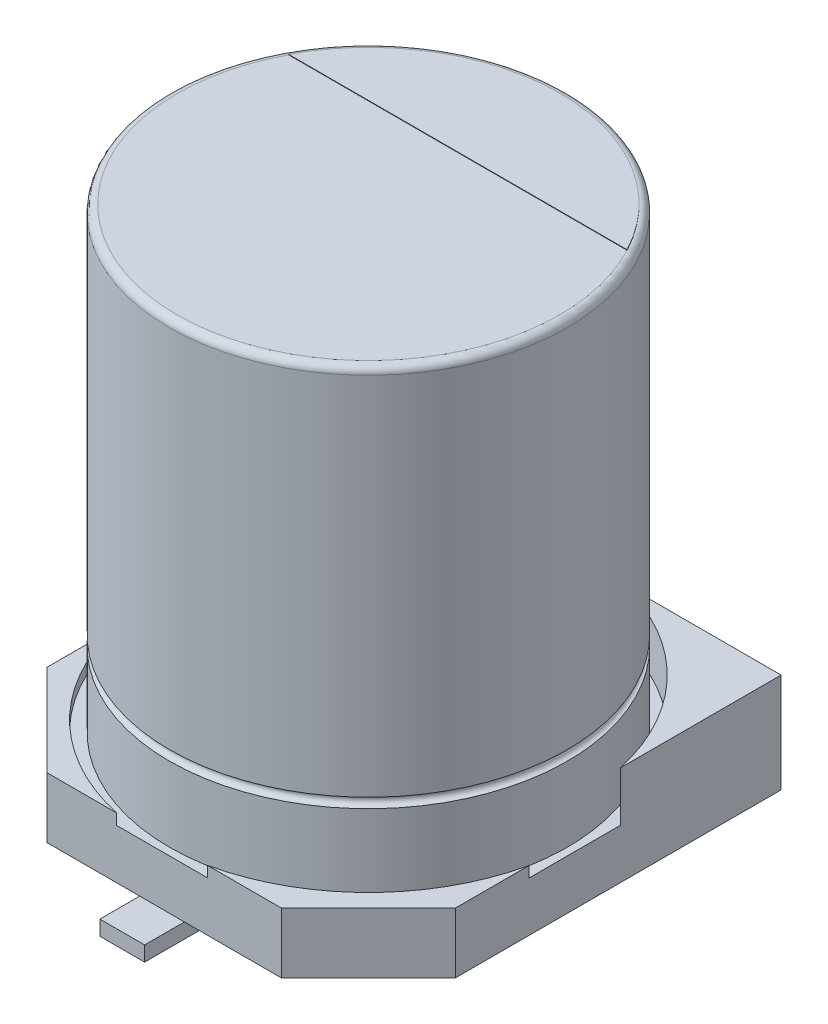
SolidWorks part; units mm, degrees
ref_plane "Front Plane" through (0, 0, 0) normal (0, 0, 1) x (1, 0, 0)
ref_plane "Top Plane" through (0, 0, 0) normal (0, 1, 0) x (1, 0, 0)
ref_plane "Right Plane" through (0, 0, 0) normal (1, 0, 0) x (0, 0, -1)
sketch "Sketch1" plane through (0, 0, 0) normal (0, 1, 0) x (1, 0, 0)
  line L0 (-4.15, 4.15) -> (4.15, 4.15)
  line L1 (4.15, 4.15) -> (4.15, -2.4026)
  line L2 (4.15, -2.4026) -> (2.4026, -4.15)
  line L3 (2.4026, -4.15) -> (-2.3153, -4.15)
  line L4 (-2.3153, -4.15) -> (-4.15, -2.3153)
  line L5 (-4.15, -2.3153) -> (-4.15, 4.15)
  line L6 (0, 5.1629) -> (0, -6.366) construction
  line L7 (-5.4826, 0) -> (5.3839, 0) construction
  dimension "D1" = 8.3
  dimension "D2" = 8.3
extrude "Boss-Extrude1" add sketch "Sketch1" along normal blind 2
sketch "Sketch2" plane through (0, 2, 0) normal (0, 1, 0) x (1, 0, 0)
  circle A0 centre (0, 0) radius 4.25
  dimension "D1" = 8.5
extrude "Cut-Extrude1" cut sketch "Sketch2" against normal blind 1
sketch "Sketch8" plane through (-4.15, 0, 0) normal (-1, 0, 0) x (0, 0, 1)
  line L1 (0.9165, 1.2174) -> (4.3266, 1.2174)
  line L2 (0.9165, 1.2174) -> (0.9165, 2.313)
  line L3 (0.9165, 2.313) -> (4.3266, 2.313)
  line L4 (4.3266, 1.2174) -> (4.3266, 2.313)
extrude "Cut-Extrude4" cut sketch "Sketch8" against normal up to surface (8.3 mm away)
sketch "Sketch5" plane through (0, 0, 0) normal (0, 0, 1) x (1, 0, 0)
  line L0 (0, 1) -> (0, 10.407) construction
  line L2 (0, 1) -> (-4, 1)
  line L3 (-4, 1) -> (-4, 2.5)
  line L4 (-4, 2.7) -> (-4, 10.05)
  line L5 (-3.85, 10.2) -> (0, 10.2)
  line L6 (0, 10.2) -> (0, 1)
  arc A0 (-4, 2.5) -> (-4, 2.7) centre (-4, 2.6) ccw
  arc A1 (-4, 10.05) -> (-3.85, 10.2) centre (-3.85, 10.05) cw
  dimension "D1" = 0.1
  dimension "D4" = 0.15
  dimension "D2" = 9.2
  dimension "D3" = 1.5
revolve "Revolve1" add sketch "Sketch5" angle 360 about L6
sketch "Sketch6" plane through (0, 10.2, 0) normal (0, 1, 0) x (1, 0, 0)
  line L0 (-3.4036, 1.7994) -> (3.4036, 1.7994)
  circle A0 centre (0, 0) radius 3.85 construction
  arc A1 (3.4036, 1.7994) -> (-3.4036, 1.7994) centre (0, 0) ccw
extrude "Boss-Extrude4" add sketch "Sketch6" along normal blind 0.01
sketch "Sketch9" plane through (0, 0, 0) normal (0, -1, 0) x (1, 0, 0)
  line L0 (0, 4.3805) -> (0, -0.5544) construction
  line L1 (4.5693, 0) -> (-4.8861, 0) construction
  line L2 (0.45, -4.95) -> (-0.45, -4.95)
  line L3 (0.45, 1.55) -> (-0.45, 1.55)
  line L4 (0.45, 1.55) -> (0.45, 4.95)
  line L5 (0.45, 4.95) -> (-0.45, 4.95)
  line L6 (-0.45, 1.55) -> (-0.45, 4.95)
  line L7 (0.45, 1.55) -> (-0.45, 4.95) construction
  line L8 (0.45, 4.95) -> (-0.45, 1.55) construction
  line L9 (-0.45, -1.55) -> (-0.45, -4.95)
  line L10 (0.45, -1.55) -> (-0.45, -1.55)
  line L11 (0.45, -1.55) -> (0.45, -4.95)
  point P5 (0, 3.25)
  dimension "D1" = 1.55
  dimension "D2" = 3.4
  dimension "D3" = 0.9
extrude "Boss-Extrude5" add sketch "Sketch9" along normal blind 0.3
